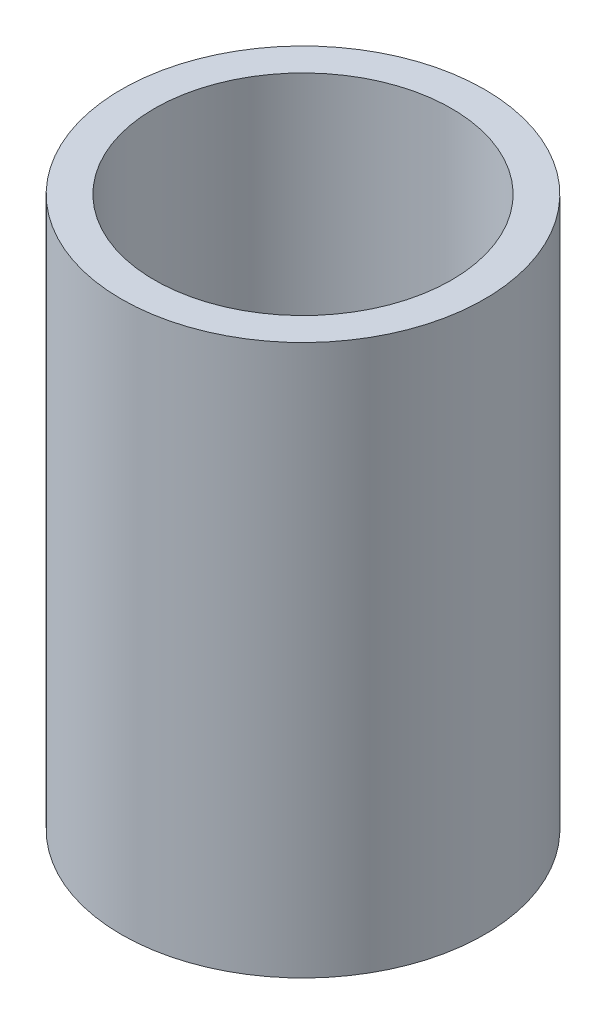
SolidWorks part; units mm, degrees
material "AISI 304"
ref_plane "Front" through (0, 0, 0) normal (0, 0, 1) x (1, 0, 0)
ref_plane "Top" through (0, 0, 0) normal (0, 1, 0) x (1, 0, 0)
ref_plane "Right" through (0, 0, 0) normal (1, 0, 0) x (0, 0, -1)
sketch "Sketch1" plane through (0, 0, 0) normal (0, 1, 0) x (1, 0, 0)
  circle A0 centre (0, 0) radius 16.5
  dimension "D1" = 33
extrude "Extrude-Thin1" add sketch "Sketch1" along normal mid plane 50 thin thin type one direction reverse wall 3
